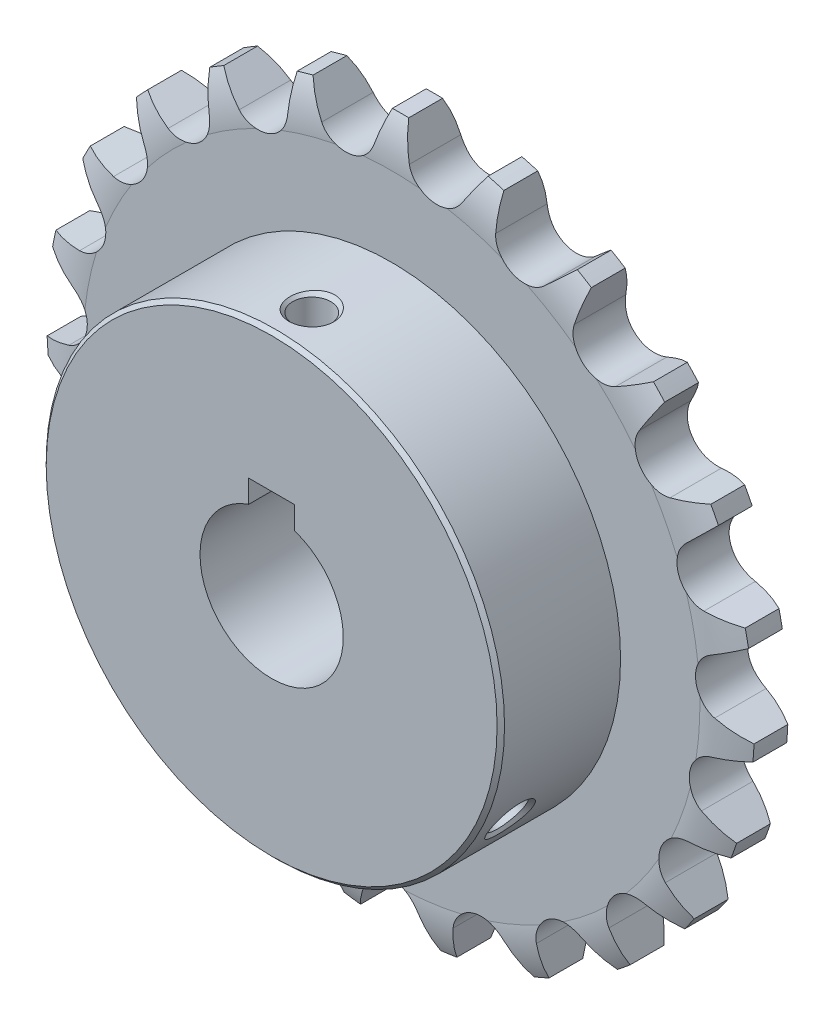
SolidWorks part; units mm, degrees
ref_plane "Front Plane" through (0, 0, 0) normal (0, 0, 1) x (1, 0, 0)
ref_plane "Top Plane" through (0, 0, 0) normal (0, 1, 0) x (1, 0, 0)
ref_plane "Right Plane" through (0, 0, 0) normal (1, 0, 0) x (0, 0, -1)
ref_plane "Plane1" through (0, 0, 0) normal (1, 0, 0) x (0, 0, -1)
sketch "Sketch1" plane through (0, 0, 0) normal (1, 0, 0) x (0, 0, -1)
  line L0 (-30, 39.35) -> (-30, 12.5)
  line L1 (-30, 12.5) -> (0, 12.5)
  line L2 (0, 12.5) -> (0, 53.85)
  line L3 (-1.6, 61.75) -> (-7.5, 61.75)
  line L4 (-9.1, 53.85) -> (-9.1, 40)
  line L5 (-9.1, 40) -> (-29.35, 40)
  line L6 (-29.35, 40) -> (-30, 39.35)
  line L7 (0, 0) -> (-4.55, 0) construction
  arc A0 (0, 53.85) -> (-1.6, 61.75) centre (-15.976, 54.7264) ccw
  arc A1 (-7.5, 61.75) -> (-9.1, 53.85) centre (6.876, 54.7264) ccw
revolve "Revolve1" add sketch "Sketch1" angle 360 about L7
ref_plane "Plane2" through (0, 0, 0) normal (0, 0, 1) x (1, 0, 0)
sketch "Sketch2" plane through (0, 0, 0) normal (0, 0, 1) x (1, 0, 0)
  line L0 (-61.7035, -2.7887) -> (-61.5086, -5.6392)
  line L1 (-61.5086, -5.6392) -> (-55.9432, -6.9062)
  line L2 (-54.0632, -15.9534) -> (-58.663, -19.3327)
  line L3 (-58.663, -19.3327) -> (-57.7062, -22.0249)
  line L4 (-57.7062, -22.0249) -> (-52.0054, -21.7434)
  line L5 (-47.7542, -29.9479) -> (-51.2717, -34.4429)
  line L6 (-51.2717, -34.4429) -> (-49.6241, -36.7771)
  line L7 (-49.6241, -36.7771) -> (-44.2106, -34.968)
  line L8 (-37.9035, -41.7212) -> (-40.0778, -46.9986)
  line L9 (-40.0778, -46.9986) -> (-37.8615, -48.8017)
  line L10 (-37.8615, -48.8017) -> (-33.1369, -45.5991)
  line L11 (-25.2417, -50.4003) -> (-25.9116, -56.0687)
  line L12 (-25.9116, -56.0687) -> (-23.291, -57.2069)
  line L13 (-23.291, -57.2069) -> (-19.6056, -52.8484)
  line L14 (-10.7078, -55.3415) -> (-9.8236, -60.9803)
  line L15 (-9.8236, -60.9803) -> (-6.993, -61.3694)
  line L16 (-6.993, -61.3694) -> (-4.6202, -56.1782)
  line L17 (4.6202, -56.1782) -> (6.993, -61.3694)
  line L18 (6.993, -61.3694) -> (9.8236, -60.9803)
  line L19 (9.8236, -60.9803) -> (10.7078, -55.3415)
  line L20 (19.6056, -52.8484) -> (23.291, -57.2069)
  line L21 (23.291, -57.2069) -> (25.9116, -56.0687)
  line L22 (25.9116, -56.0687) -> (25.2417, -50.4003)
  line L23 (33.1369, -45.5991) -> (37.8615, -48.8017)
  line L24 (37.8615, -48.8017) -> (40.0778, -46.9986)
  line L25 (40.0778, -46.9986) -> (37.9035, -41.7212)
  line L26 (44.2106, -34.968) -> (49.6241, -36.7771)
  line L27 (49.6241, -36.7771) -> (51.2717, -34.4429)
  line L28 (51.2717, -34.4429) -> (47.7542, -29.9479)
  line L29 (52.0054, -21.7434) -> (57.7062, -22.0249)
  line L30 (57.7062, -22.0249) -> (58.663, -19.3327)
  line L31 (58.663, -19.3327) -> (54.0632, -15.9534)
  line L32 (55.9432, -6.9062) -> (61.5086, -5.6392)
  line L33 (61.5086, -5.6392) -> (61.7035, -2.7887)
  line L34 (61.7035, -2.7887) -> (56.3625, -0.7757)
  line L35 (55.7319, 8.4432) -> (60.7491, 11.1647)
  line L36 (60.7491, 11.1647) -> (60.1678, 13.9621)
  line L37 (60.1678, 13.9621) -> (54.4817, 14.4595)
  line L38 (51.3873, 23.1664) -> (55.4842, 27.1406)
  line L39 (55.4842, 27.1406) -> (54.1697, 29.6774)
  line L40 (54.1697, 29.6774) -> (48.5603, 28.6223)
  line L41 (43.2315, 36.1715) -> (46.1042, 41.1036)
  line L42 (46.1042, 41.1036) -> (44.154, 43.1917)
  line L43 (44.154, 43.1917) -> (39.0374, 40.6623)
  line L44 (31.8694, 46.4938) -> (33.3049, 52.0181)
  line L45 (33.3049, 52.0181) -> (30.8637, 53.5027)
  line L46 (30.8637, 53.5027) -> (26.6192, 49.6866)
  line L47 (18.1437, 53.368) -> (18.0356, 59.0747)
  line L48 (18.0356, 59.0747) -> (15.2843, 59.8456)
  line L49 (15.2843, 59.8456) -> (12.2268, 55.0258)
  line L50 (3.0724, 56.2841) -> (1.4286, 61.75)
  line L51 (1.4286, 61.75) -> (-1.4286, 61.75)
  line L52 (-1.4286, 61.75) -> (-3.0724, 56.2841)
  line L53 (-12.2268, 55.0258) -> (-15.2843, 59.8456)
  line L54 (-15.2843, 59.8456) -> (-18.0356, 59.0747)
  line L55 (-18.0356, 59.0747) -> (-18.1437, 53.368)
  line L56 (-26.6192, 49.6866) -> (-30.8637, 53.5027)
  line L57 (-30.8637, 53.5027) -> (-33.3049, 52.0181)
  line L58 (-33.3049, 52.0181) -> (-31.8694, 46.4938)
  line L59 (-39.0374, 40.6623) -> (-44.154, 43.1917)
  line L60 (-44.154, 43.1917) -> (-46.1042, 41.1036)
  line L61 (-46.1042, 41.1036) -> (-43.2315, 36.1715)
  line L62 (-48.5603, 28.6223) -> (-54.1697, 29.6774)
  line L63 (-54.1697, 29.6774) -> (-55.4842, 27.1406)
  line L64 (-55.4842, 27.1406) -> (-51.3873, 23.1664)
  line L65 (-54.4817, 14.4595) -> (-60.1678, 13.9621)
  line L66 (-60.1678, 13.9621) -> (-60.7491, 11.1647)
  line L67 (-60.7491, 11.1647) -> (-55.7319, 8.4432)
  line L68 (-56.3625, -0.7757) -> (-61.7035, -2.7887)
  circle A0 centre (0, 0) radius 116.58
  arc A1 (-55.9432, -6.9062) -> (-54.0632, -15.9534) centre (-57.0708, -11.8595) cw
  arc A2 (-52.0054, -21.7434) -> (-47.7542, -29.9479) centre (-51.7548, -26.8172) cw
  arc A3 (-44.2106, -34.968) -> (-37.9035, -41.7212) centre (-42.6004, -39.786) cw
  arc A4 (-33.1369, -45.5991) -> (-25.2417, -50.4003) centre (-30.2865, -49.8041) cw
  arc A5 (-19.6056, -52.8484) -> (-10.7078, -55.3415) centre (-15.7265, -56.1284) cw
  arc A6 (-4.6202, -56.1782) -> (4.6202, -56.1782) centre (0, -58.29) cw
  arc A7 (10.7078, -55.3415) -> (19.6056, -52.8484) centre (15.7265, -56.1284) cw
  arc A8 (25.2417, -50.4003) -> (33.1369, -45.5991) centre (30.2865, -49.8041) cw
  arc A9 (37.9035, -41.7212) -> (44.2106, -34.968) centre (42.6004, -39.786) cw
  arc A10 (47.7542, -29.9479) -> (52.0054, -21.7434) centre (51.7548, -26.8172) cw
  arc A11 (54.0632, -15.9534) -> (55.9432, -6.9062) centre (57.0708, -11.8595) cw
  arc A12 (56.3625, -0.7757) -> (55.7319, 8.4432) centre (58.1541, 3.9779) cw
  arc A13 (54.4817, 14.4595) -> (51.3873, 23.1664) centre (54.9244, 19.5201) cw
  arc A14 (48.5603, 28.6223) -> (43.2315, 36.1715) centre (47.6212, 33.6147) cw
  arc A15 (39.0374, 40.6623) -> (31.8694, 46.4938) centre (36.7861, 45.2162) cw
  arc A16 (26.6192, 49.6866) -> (18.1437, 53.368) centre (23.2228, 53.4642) cw
  arc A17 (12.2268, 55.0258) -> (3.0724, 56.2841) centre (7.9372, 57.7471) cw
  arc A18 (-3.0724, 56.2841) -> (-12.2268, 55.0258) centre (-7.9372, 57.7471) cw
  arc A19 (-18.1437, 53.368) -> (-26.6192, 49.6866) centre (-23.2228, 53.4642) cw
  arc A20 (-31.8694, 46.4938) -> (-39.0374, 40.6623) centre (-36.7861, 45.2162) cw
  arc A21 (-43.2315, 36.1715) -> (-48.5603, 28.6223) centre (-47.6212, 33.6147) cw
  arc A22 (-51.3873, 23.1664) -> (-54.4817, 14.4595) centre (-54.9244, 19.5201) cw
  arc A23 (-55.7319, 8.4432) -> (-56.3625, -0.7757) centre (-58.1541, 3.9779) cw
extrude "Cut-Extrude1" cut sketch "Sketch2" against normal blind 9.2 and the other way blind 9.2
ref_plane "Plane3" through (0, 0, 23) normal (0, 0, 1) x (1, 0, 0)
sketch "Sketch3" plane through (0, 0, 23) normal (0, 0, 1) x (1, 0, 0)
  line L0 (0, 12) -> (-3.3235, 12)
  line L1 (-3.3235, 12) -> (-3.3235, 39.3235)
  line L2 (-3.3235, 39.3235) -> (-4, 40)
  line L3 (-4, 40) -> (0, 40)
  line L4 (0, 40) -> (0, 12)
  line L5 (0, 40) -> (0, 12) construction
revolve "Cut-Revolve1" cut sketch "Sketch3" angle 360 about L5
cosmetic thread "Cosmetic Thread1" parameters "D1"=24.2, "D2"=8
ref_plane "Plane4" through (0, 0, 23) normal (0, 0, 1) x (1, 0, 0)
sketch "Sketch4" plane through (0, 0, 23) normal (0, 0, 1) x (1, 0, 0)
  line L0 (0, 0) -> (1.6618, 2.8782)
  line L1 (1.6618, 2.8782) -> (35.7169, -16.7835)
  line L2 (35.7169, -16.7835) -> (36.641, -16.5359)
  line L3 (36.641, -16.5359) -> (34.641, -20)
  line L4 (34.641, -20) -> (0, 0)
  line L5 (34.641, -20) -> (0, 0) construction
revolve "Cut-Revolve2" cut sketch "Sketch4" angle 360 about L5
cosmetic thread "Cosmetic Thread2" parameters "D1"=27.5, "D2"=8
ref_plane "Plane5" through (0, 0, 0) normal (0, 0, 1) x (1, 0, 0)
sketch "Sketch5" plane through (0, 0, 0) normal (0, 0, 1) x (1, 0, 0)
  line L0 (-4, 15.8) -> (-4, 0)
  line L1 (-4, 0) -> (4, 0)
  line L2 (4, 0) -> (4, 15.8)
  line L3 (4, 15.8) -> (-4, 15.8)
extrude "Cut-Extrude2" cut sketch "Sketch5" along normal blind 30
ref_plane "Plane6" through (0, 0, 4.5) normal (0, 0, -1) x (-1, 0, 0)
sketch "Sketch6" plane through (0, 0, 4.5) normal (0, 0, -1) x (-1, 0, 0)
  circle A0 centre (0, 0) radius 58.5
